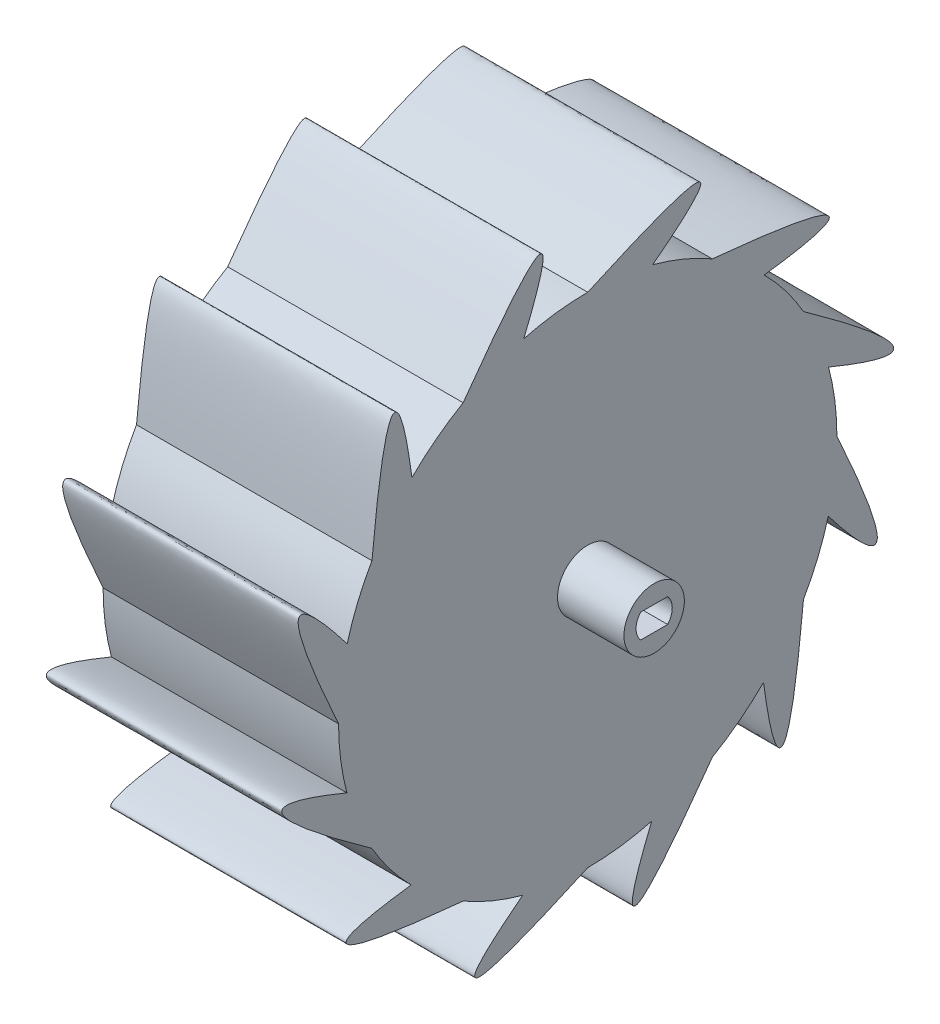
SolidWorks part; units mm, degrees
material "Nylon 101"
ref_plane "Front Plane" through (0, 0, 0) normal (0, 0, 1) x (1, 0, 0)
ref_plane "Top Plane" through (0, 0, 0) normal (0, 1, 0) x (1, 0, 0)
ref_plane "Right Plane" through (0, 0, 0) normal (1, 0, 0) x (0, 0, -1)
sketch "Sketch1" plane through (0, 0, 0) normal (1, 0, 0) x (0, 0, -1)
  circle A0 centre (0, 0) radius 5
  circle A1 centre (0, 0) radius 32.5
  dimension "D1" = 65
  dimension "D2" = 10
extrude "Boss-Extrude1" add sketch "Sketch1" against normal blind 35
sketch "Sketch2" plane through (-35, 0, 0) normal (-1, 0, 0) x (0, 0, 1)
  circle A0 centre (0, 0) radius 8.5
  circle A1 centre (0, 0) radius 1
  dimension "D1" = 2
  dimension "D2" = 17
extrude "Boss-Extrude2" add sketch "Sketch2" against normal blind 1 separate body
sketch "Sketch3" plane through (-35, 0, 0) normal (-1, 0, 0) x (0, 0, 1)
  line L0 (0, 0) -> (13.5, 0) construction
  line L1 (12.8938, 4) -> (20.6155, 4)
  line L2 (7.7886, -11.0267) -> (10.1748, -18.3705)
  line L3 (20.6155, -4) -> (12.8938, -4)
  line L4 (2.5663, -20.8426) -> (0.1802, -13.4988)
  line L5 (-8.0802, -10.8149) -> (-14.3272, -15.3536)
  line L6 (-19.0295, -8.8814) -> (-12.7824, -4.3427)
  line L7 (-12.7824, 4.3427) -> (-19.0295, 8.8814)
  line L8 (-14.3272, 15.3536) -> (-8.0802, 10.8149)
  line L9 (0.1802, 13.4988) -> (2.5663, 20.8426)
  line L10 (10.1748, 18.3705) -> (7.7886, 11.0267)
  line L11 (-2.2361, 2) -> (2.2361, 2)
  line L12 (-2.2361, -2) -> (2.2361, -2)
  circle A0 centre (0, 0) radius 32.5
  arc A1 (2.5663, -20.8426) -> (10.1748, -18.3705) centre (0, 0) ccw
  arc A2 (0.1802, -13.4988) -> (7.7886, -11.0267) centre (0, 0) ccw
  arc A3 (-12.7824, -4.3427) -> (-8.0802, -10.8149) centre (0, 0) ccw
  arc A4 (-19.0295, -8.8814) -> (-14.3272, -15.3536) centre (0, 0) ccw
  arc A5 (-14.3272, 15.3536) -> (-19.0295, 8.8814) centre (0, 0) ccw
  arc A6 (-8.0802, 10.8149) -> (-12.7824, 4.3427) centre (0, 0) ccw
  arc A7 (10.1748, 18.3705) -> (2.5663, 20.8426) centre (0, 0) ccw
  arc A8 (7.7886, 11.0267) -> (0.1802, 13.4988) centre (0, 0) ccw
  arc A9 (20.6155, -4) -> (20.6155, 4) centre (0, 0) ccw
  arc A10 (12.8938, -4) -> (12.8938, 4) centre (0, 0) ccw
  arc A11 (-2.2361, 2) -> (-2.2361, -2) centre (0, 0) ccw
  arc A12 (2.2361, -2) -> (2.2361, 2) centre (0, 0) ccw
  point P29 (0, 0)
  dimension "D1" = 27
  dimension "D2" = 42
  dimension "D4" = 6
  dimension "D3" = 4
  dimension "D6" = 2
  dimension "D5" = 5
extrude "Boss-Extrude4" add sketch "Sketch3" along normal blind 2
sketch "Sketch4" plane through (-37, 0, 0) normal (-1, 0, 0) x (0, 0, 1)
  circle A0 centre (0, 0) radius 32.5 construction
  circle A1 centre (0, 0) radius 32.5
  circle A2 centre (0, 0) radius 5 construction
  circle A3 centre (0, 0) radius 5
extrude "Boss-Extrude5" add sketch "Sketch4" along normal blind 2
sketch "Sketch5" plane through (-37, 0, 0) normal (-1, 0, 0) x (0, 0, 1)
  line L0 (2.2361, 2) -> (-2.2361, 2) construction
  line L1 (2.2361, 2) -> (-2.2361, 2)
  line L2 (-2.2361, -2) -> (2.2361, -2) construction
  line L3 (-2.2361, -2) -> (2.2361, -2)
  arc A0 (-2.2361, 2) -> (-2.2361, -2) centre (0, 0) ccw construction
  arc A1 (-2.2361, 2) -> (-2.2361, -2) centre (0, 0) ccw
  arc A2 (2.2361, -2) -> (2.2361, 2) centre (0, 0) ccw construction
  arc A3 (2.2361, -2) -> (2.2361, 2) centre (0, 0) ccw
  circle A4 centre (0, 0) radius 5
  dimension "D1" = 10
extrude "Boss-Extrude6" add sketch "Sketch5" against normal blind 48 separate body
sketch "Sketch6" plane through (-39, 0, 0) normal (-1, 0, 0) x (0, 0, 1)
  circle A0 centre (0, 0) radius 32.5
  arc A62 (-29.2454, 29.1191) -> (-35.7409, 20.635) centre (0, 0) ccw
  arc A63 (-39.8868, 10.5952) -> (-41.27, 0) centre (0, 0) ccw
  arc A64 (-39.8406, -10.7677) -> (-35.7409, -20.635) centre (0, 0) ccw
  arc A65 (-29.1191, -29.2454) -> (-20.635, -35.7409) centre (0, 0) ccw
  arc A66 (-10.5952, -39.8868) -> (0, -41.27) centre (0, 0) ccw
  arc A67 (10.7677, -39.8406) -> (20.635, -35.7409) centre (0, 0) ccw
  arc A68 (29.2454, -29.1191) -> (35.7409, -20.635) centre (0, 0) ccw
  arc A69 (39.8868, -10.5952) -> (41.27, 0) centre (0, 0) ccw
  arc A70 (39.8406, 10.7677) -> (35.7409, 20.635) centre (0, 0) ccw
  arc A71 (29.1191, 29.2454) -> (20.635, 35.7409) centre (0, 0) ccw
  arc A72 (10.5952, 39.8868) -> (0, 41.27) centre (0, 0) ccw
  arc A73 (-10.7677, 39.8406) -> (-20.635, 35.7409) centre (0, 0) ccw
  spline S0 degree 2 poles (0, 41.27) (-30.9282, 55.3328) (-10.7677, 39.8406) knots 0 0 0 1 1 1
  spline S1 degree 2 poles (20.635, 35.7409) (0.8818, 63.3837) (10.5952, 39.8868) knots 0 0 0 1 1 1
  spline S2 degree 2 poles (35.7409, 20.635) (32.4555, 54.451) (29.1191, 29.2454) knots 0 0 0 1 1 1
  spline S3 degree 2 poles (41.27, 0) (55.3328, 30.9282) (39.8406, 10.7677) knots 0 0 0 1 1 1
  spline S4 degree 2 poles (35.7409, -20.635) (63.3837, -0.8818) (39.8868, -10.5952) knots 0 0 0 1 1 1
  spline S5 degree 2 poles (20.635, -35.7409) (54.451, -32.4555) (29.2454, -29.1191) knots 0 0 0 1 1 1
  spline S6 degree 2 poles (0, -41.27) (30.9282, -55.3328) (10.7677, -39.8406) knots 0 0 0 1 1 1
  spline S7 degree 2 poles (-20.635, -35.7409) (-0.8818, -63.3837) (-10.5952, -39.8868) knots 0 0 0 1 1 1
  spline S8 degree 2 poles (-35.7409, -20.635) (-32.4555, -54.451) (-29.1191, -29.2454) knots 0 0 0 1 1 1
  spline S9 degree 2 poles (-41.27, 0) (-55.3328, -30.9282) (-39.8406, -10.7677) knots 0 0 0 1 1 1
  spline S10 degree 2 poles (-35.7409, 20.635) (-63.3837, 0.8818) (-39.8868, 10.5952) knots 0 0 0 1 1 1
  spline S11 degree 2 poles (-20.635, 35.7409) (-54.451, 32.4555) (-29.2454, 29.1191) knots 0 0 0 1 1 1
  point P43 (0, 0)
  point P71 (0, 0)
  point P82 (0, 0)
  point P83 (0, 0)
  point P99 (0, 0)
  dimension "D1" = 65
  dimension "D2" = 8.77
extrude "Boss-Extrude7" add sketch "Sketch6" against normal blind 39
